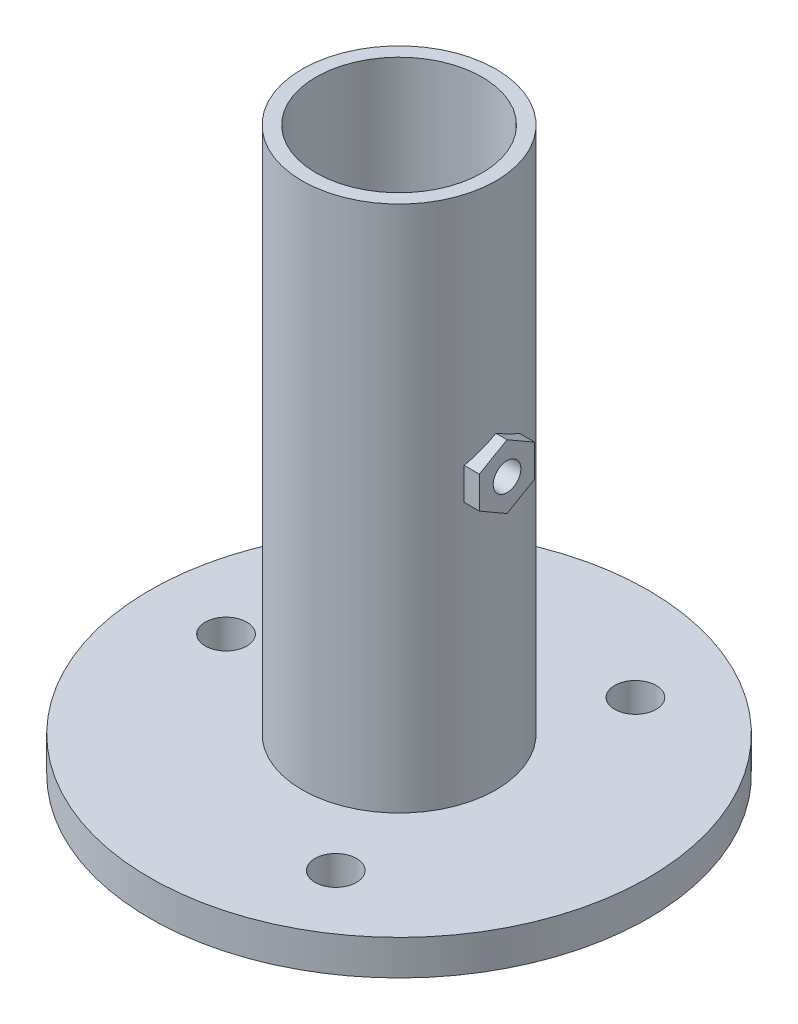
SolidWorks part; units mm, degrees
ref_plane "Front Plane" through (0, 0, 0) normal (0, 0, 1) x (1, 0, 0)
ref_plane "Top Plane" through (0, 0, 0) normal (0, 1, 0) x (1, 0, 0)
ref_plane "Right Plane" through (0, 0, 0) normal (1, 0, 0) x (0, 0, -1)
sketch "Sketch2" plane through (0, 0, 0) normal (0, 1, 0) x (1, 0, 0)
  circle A0 centre (0, 0) radius 17.5
  dimension "D1" = 35
extrude "Boss-Extrude2" add sketch "Sketch2" along normal blind 101.6
sketch "Sketch3" plane through (0, 0, 0) normal (0, -1, 0) x (-1, 0, 0)
  circle A0 centre (0, 0) radius 45
  dimension "D1" = 90
extrude "Boss-Extrude3" add sketch "Sketch3" against normal blind 6.35
sketch "Sketch4" plane through (0, 0, 0) normal (0, -1, 0) x (-1, 0, 0)
  circle A0 centre (0, 0) radius 9
  dimension "D1" = 18
extrude "Cut-Extrude1" cut sketch "Sketch4" against normal offset from surface (95.25 mm away) 6.35 up to face at (0, 101.6, 17.5)
sketch "Sketch5" plane through (0, 101.6, 0) normal (0, 1, 0) x (1, 0, 0)
  circle A0 centre (0, 0) radius 15
  dimension "D1" = 30
extrude "Cut-Extrude2" cut sketch "Sketch5" against normal offset from surface (96.6 mm away) 5 up to face at (0, 0, -9)
sketch "Sketch6" plane through (0, 0, 0) normal (1, 0, 0) x (0, 0, -1)
  line L0 (0, 6.35) -> (0, 56.35) construction
  line L1 (45, 6.35) -> (-45, 6.35) construction
  circle A0 centre (0, 56.35) radius 2.5
  dimension "D2" = 5
  dimension "D1" = 50
extrude "Cut-Extrude3" cut sketch "Sketch6" along normal through all
sketch "Sketch7" plane through (0, 6.35, 0) normal (0, 1, 0) x (1, 0, 0)
  line L0 (0, 0) -> (17.5, 0) construction
  circle A0 centre (0, 0) radius 17.5 construction
  point P2 (0, 17.5)
  point P3 (0, 0)
  point P4 (17.5, 0)
sketch3d "3DSketch2"
sketch "Sketch8" plane through (17.5, 0, 0) normal (-1, 0, 0) x (0, 0, 1)
  line L0 (45, 6.35) -> (-45, 6.35) construction
  line L1 (-5, 53.4632) -> (0, 50.5765)
  line L2 (0, 50.5765) -> (5, 53.4632)
  line L3 (5, 53.4632) -> (5, 59.2368)
  line L4 (5, 59.2368) -> (0, 62.1235)
  line L5 (0, 62.1235) -> (-5, 59.2368)
  line L6 (-5, 59.2368) -> (-5, 53.4632)
  circle A0 centre (0, 56.35) radius 5 construction
  circle A1 centre (0, 56.35) radius 2.5 construction
  circle A2 centre (0, 56.35) radius 2.5
  dimension "D2" = 10
  dimension "D1" = 90
  dimension "D3" = 0
extrude "Boss-Extrude4" add sketch "Sketch8" along normal blind 5 and the other way blind 2
sketch "Sketch9" plane through (0, 6.35, 0) normal (0, 1, 0) x (1, 0, 0)
  line L0 (-45, 0) -> (-31.25, 0) construction
  circle A0 centre (0, 0) radius 45 construction
  circle A1 centre (-31.25, 0) radius 3.75
  dimension "D2" = 7.5
  dimension "D1" = 13.75
extrude "Cut-Extrude4" cut sketch "Sketch9" against normal through all
pattern_circular "CirPattern1" count 3 every 120 about axis through (0, 0, 0) along (0, 1, 0) of "Cut-Extrude4"
